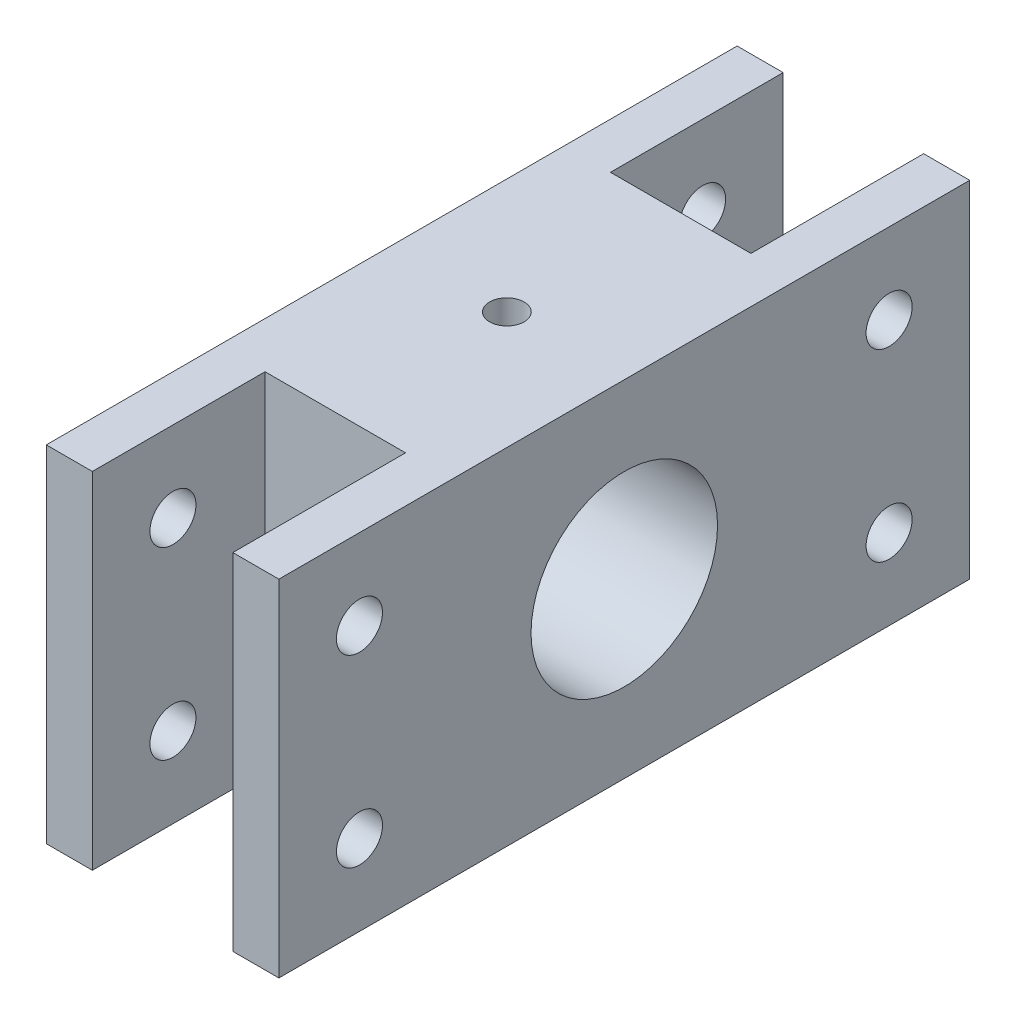
SolidWorks part; units mm, degrees
ref_plane "정면" through (0, 0, 0) normal (0, 0, 1) x (1, 0, 0)
ref_plane "윗면" through (0, 0, 0) normal (0, 1, 0) x (1, 0, 0)
ref_plane "우측면" through (0, 0, 0) normal (1, 0, 0) x (0, 0, -1)
sketch "스케치1" plane through (0, 0, 0) normal (1, 0, 0) x (0, 0, -1)
  line L0 (0, 24.1656) -> (0, -23.006) construction
  line L1 (-30, 15) -> (30, 15)
  line L2 (-30, 15) -> (-30, -15)
  line L3 (-30, -15) -> (30, -15)
  line L4 (30, 15) -> (30, -15)
  line L5 (-30, 15) -> (30, -15) construction
  line L6 (-30, -15) -> (30, 15) construction
  line L7 (-42.7163, 0) -> (48.1791, 0) construction
  circle A0 centre (-23, 8) radius 2
  circle A1 centre (-23, -8) radius 2
  circle A2 centre (23, -8) radius 2
  circle A3 centre (23, 8) radius 2
  point P0 (0, 0)
  dimension "D3" = 4
  dimension "D5" = 7
  dimension "D1" = 60
  dimension "D2" = 30
  dimension "D4" = 7
extrude "보스-돌출1" add sketch "스케치1" along normal blind 20.2
sketch "스케치2" plane through (0, 15, 0) normal (0, 1, 0) x (1, 0, 0)
  line L0 (-9.7231, 0) -> (28.9218, 0) construction
  line L1 (4, 30) -> (4, 15)
  line L2 (20.2, 30) -> (0, 30) construction
  line L3 (4, 15) -> (16.2, 15)
  line L4 (16.2, 30) -> (16.2, 15)
  line L5 (10.1, 32.2306) -> (10.1, -33.7445) construction
  line L6 (0, 30) -> (0, -30) construction
  line L7 (20.2, 30) -> (20.2, -30) construction
  line L8 (4, 30) -> (16.2, 30)
  line L9 (4, -30) -> (4, -15)
  line L10 (4, -15) -> (16.2, -15)
  line L11 (16.2, -30) -> (16.2, -15)
  line L12 (4, -30) -> (16.2, -30)
  point P11 (10.1, 15)
  dimension "D1" = 4
  dimension "D2" = 4
  dimension "D3" = 15
extrude "컷-돌출1" cut sketch "스케치2" against normal through all
sketch "스케치3" plane through (0, 0, 0) normal (-1, 0, 0) x (0, 0, 1)
  circle A0 centre (0, 0) radius 8.1
  dimension "D1" = 16.2
extrude "컷-돌출2" cut sketch "스케치3" against normal through all
sketch "스케치4" plane through (0, 15, 0) normal (0, 1, 0) x (1, 0, 0)
  circle A0 centre (10, 0) radius 1.5
  dimension "D1" = 3
extrude "컷-돌출3" cut sketch "스케치4" against normal through all
